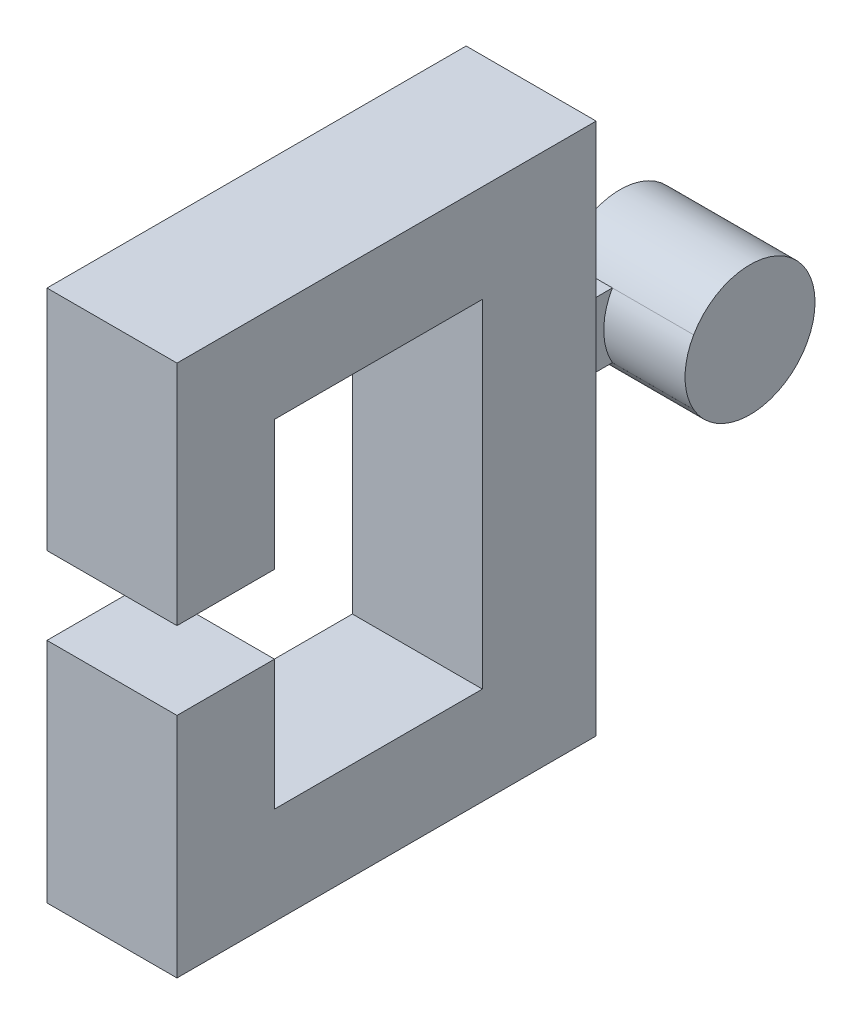
SolidWorks part; units mm, degrees
material "ASTM A36 Steel"
ref_plane "Front Plane" through (0, 0, 0) normal (1, 0, 0) x (0, 1, 0)
ref_plane "Top Plane" through (0, 0, 0) normal (0, 0, 1) x (0, 1, 0)
ref_plane "Right Plane" through (0, 0, 0) normal (0, 1, 0) x (-1, 0, 0)
sketch "Sketch1" plane through (0, 0, 0) normal (1, 0, 0) x (0, 1, 0)
  line L0 (0, 0) -> (44.4246, 0)
  line L2 (0, 0) -> (0, -81.8896)
  line L4 (104.0384, 0) -> (104.0384, -81.8896)
  line L5 (44.4246, 0) -> (44.4246, -19.05)
  line L6 (44.4246, -19.05) -> (19.05, -19.05)
  line L7 (19.05, -19.05) -> (19.05, -59.6646)
  line L8 (19.05, -59.6646) -> (84.9884, -59.6646)
  line L9 (84.9884, -59.6646) -> (84.9884, -19.05)
  line L10 (84.9884, -19.05) -> (59.6138, -19.05)
  line L11 (59.6138, -19.05) -> (59.6138, 0)
  line L12 (59.6138, 0) -> (104.0384, 0)
  line L13 (0, -81.8896) -> (45.6997, -81.8896)
  line L14 (45.6997, -81.8896) -> (45.6997, -100.9338)
  line L16 (58.3489, -100.9396) -> (58.3489, -81.8896)
  line L17 (58.3489, -81.8896) -> (104.0384, -81.8896)
  line L18 (45.6997, -81.8896) -> (58.3489, -81.8896) construction
  line L19 (52.0192, 4.8233) -> (52.0192, -124.1525) construction
  arc A2 (45.6997, -100.9338) -> (58.3489, -100.9396) centre (52.0192, -111.9498) ccw
  point P20 (52.0192, -59.6646)
  dimension "D1" = 81.8896
  dimension "D2" = 19.05
  dimension "D10" = 12.7
  dimension "D3" = 22.225
  dimension "D4" = 12.6492
  dimension "D5" = 25.3746
  dimension "D6" = 15.1892
  dimension "D7" = 19.05
  dimension "D8" = 19.05
  dimension "D9" = 26.6497
extrude "Boss-Extrude1" add sketch "Sketch1" along normal blind 25.4
sketch "Sketch2" plane through (25.4, 0, 0) normal (1, 0, 0) x (0, 1, 0)
  line L0 (45.6997, -81.8896) -> (58.3489, -81.8896)
  line L1 (58.3489, -81.8896) -> (58.3489, -100.9396)
  line L2 (58.3489, -100.9396) -> (45.6997, -100.9396) construction
  line L3 (45.6997, -100.9396) -> (45.6997, -81.8896)
  arc A0 (58.3489, -100.9396) -> (45.6997, -100.9396) centre (52.0243, -111.941) ccw
  arc A2 (45.6997, -100.9338) -> (58.3489, -100.9396) centre (52.0192, -111.9498) ccw construction
  point P9 (52.0243, -110.6601)
  point P10 (52.0243, -112.3345)
  point P11 (0, 0)
extrude "Cut-Extrude1" cut sketch "Sketch2" against normal blind 15.875
equation "\"a\"= 0.498"
equation "\"b\"= 0.999"
equation "\"c\"= 1.499"
equation "\"Clearance\"= 0.100"
equation "\"LA\" = 1"
equation "\"LB\"= 0.750"
equation "\"wB\"= \"a\""
equation "\"wC\"= 1"
equation "\"wD\"= 1"
equation "\"wE\"= 1"
equation "\"TC\"= 0.875"
equation "\"TD\"= 0.750"
equation "\"TE\"= 0.750"
equation "\"DA\"= 1"
equation "\"LC\"= \"a\" + 2 * \"b\" + \"Clearance\""
equation "\"LD\"= \"c\" + \"Clearance\""
equation "\"LE\"= \"b\""
equation "\"TopGap\"= \"LC\" - 2 * \"LE\""
equation "\"OverallWidth\"= \"LC\" + 2 * \"TD\""
equation "\"OverallHeight\"= \"TC\" + \"LD\" + \"TE\""
equation "\"PB\"= 1300"
equation "\"Sy\"= 36000"
equation "\"SF\"= 4"
equation "\"SigmaAllow\"= \"Sy\" / \"SF\""
equation "\"TB_Stress\"= \"PB\" / ( \"wB\" * \"SigmaAllow\" )"
equation "\"TB\"= IIF ( \"TB_Stress\" < 0.375in , 0.375in , \"TB_Stress\" )"
